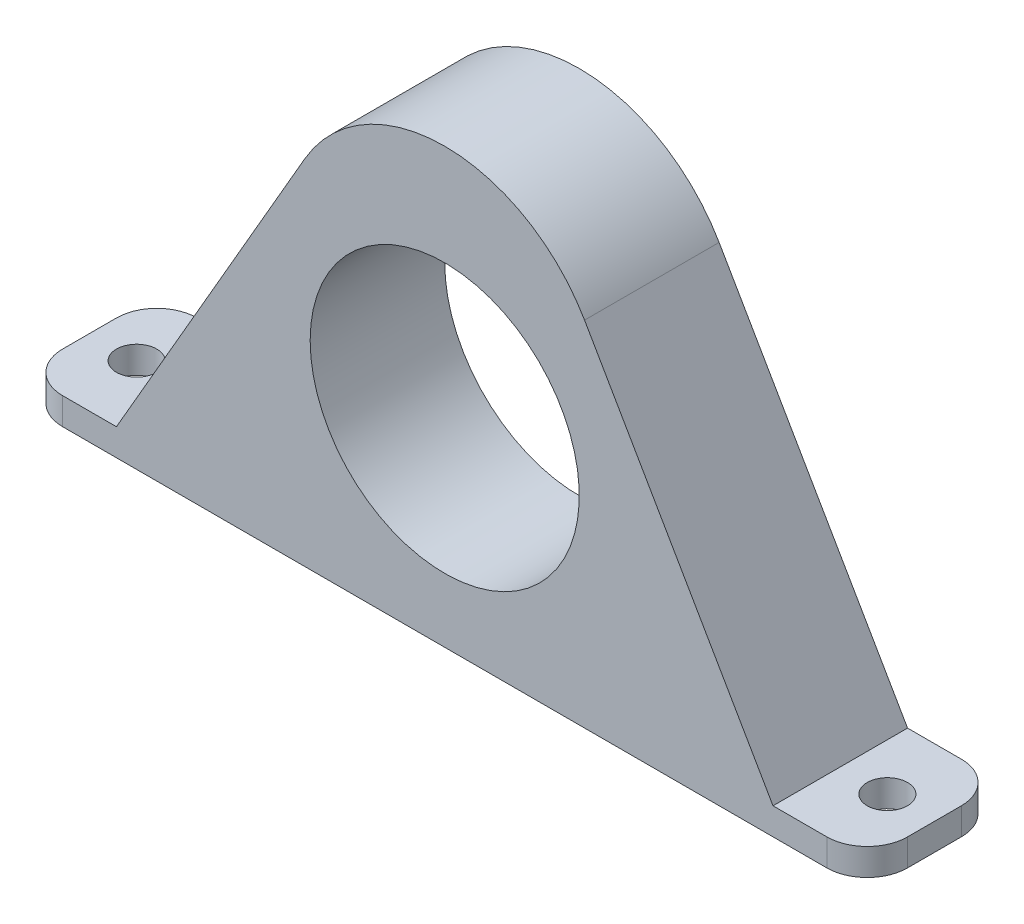
SolidWorks part; units mm, degrees
ref_plane "Alzado" through (0, 0, 0) normal (0, 0, 1) x (1, 0, 0)
ref_plane "Planta" through (0, 0, 0) normal (0, 1, 0) x (1, 0, 0)
ref_plane "Vista lateral" through (0, 0, 0) normal (1, 0, 0) x (0, 0, -1)
sketch "Croquis1" plane through (0, 0, 0) normal (0, 0, 1) x (1, 0, 0)
  line L0 (0, 0) -> (0, 29.5) construction
  line L1 (0, 0) -> (-25.5569, -14.7553) construction
  line L2 (0, 0) -> (25.5569, -14.7553) construction
  line L3 (0, 29.5) -> (-24.3961, -12.7553)
  line L4 (-25.5569, -14.7553) -> (25.5569, -14.7553)
  line L5 (0, 29.5) -> (24.3961, -12.7553)
  line L6 (-25.5569, -14.7553) -> (-31.3961, -14.7553)
  line L7 (-31.3961, -14.7553) -> (-31.3961, -12.7553)
  line L8 (-31.3961, -12.7553) -> (-24.3961, -12.7553)
  line L9 (25.5569, -14.7553) -> (31.3961, -14.7553)
  line L10 (31.3961, -14.7553) -> (31.3961, -12.7553)
  line L11 (31.3961, -12.7553) -> (24.3961, -12.7553)
  circle A0 centre (0, 0) radius 11.5
  dimension "D1" = 120
  dimension "D3" = 23
  dimension "D4" = 7
  dimension "D11" = 14.7553
  dimension "D2" = 120
  dimension "D5" = 2
  dimension "D6" = 2
  dimension "D7" = 7
  dimension "D8" = 60
  dimension "D9" = 60
  dimension "D10" = 14.75
extrude "Saliente-Extruir3" add sketch "Croquis1" along normal blind 10 contours L5 L11 L10 L9 L4 L6 L7 L8 L3
sketch "Croquis3" plane through (0, 0, 0) normal (0, 0, -1) x (-1, 0, 0)
  circle A0 centre (0, 0) radius 10
  dimension "D1" = 20
extrude "Cortar-Extruir1" cut sketch "Croquis3" against normal blind 10
fillet "Redondeo2" radius 12 1 edges at (0, 29.5, 5)
sketch "Croquis4" plane through (0, -12.7553, 0) normal (0, 1, 0) x (1, 0, 0)
  line L0 (31.3961, 0) -> (24.3961, -10) construction
  line L1 (-24.3961, 0) -> (-31.3961, -10) construction
  circle A0 centre (27.8961, -5) radius 1.5
  circle A1 centre (-27.8961, -5) radius 1.5
  dimension "D1" = 3
  dimension "D2" = 3
extrude "Cortar-Extruir2" cut sketch "Croquis4" against normal through all
fillet "Redondeo3" radius 3 4 edges at (31.3961, -13.7553, 0) (31.3961, -13.7553, 10) (-31.3961, -13.7553, 0) (-31.3961, -13.7553, 10)
